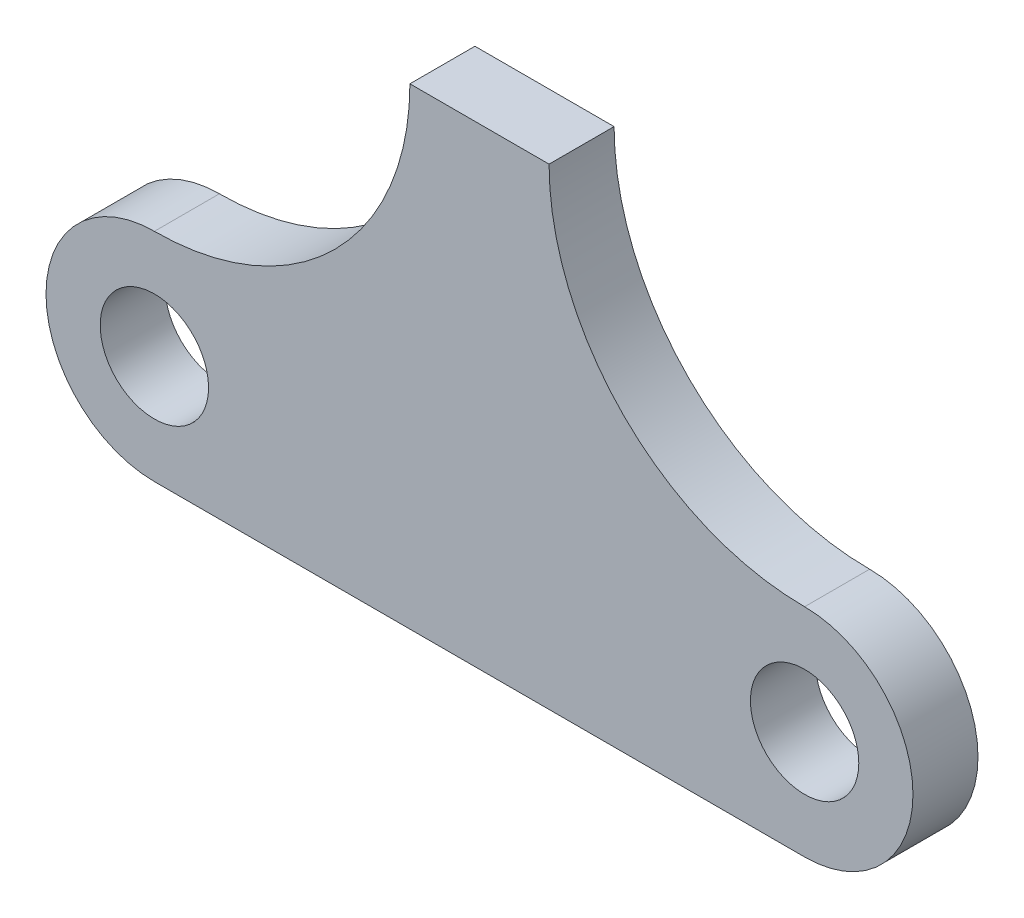
SolidWorks part; units mm, degrees
ref_plane "Front Plane" through (0, 0, 0) normal (0, 0, 1) x (1, 0, 0)
ref_plane "Top Plane" through (0, 0, 0) normal (0, 1, 0) x (1, 0, 0)
ref_plane "Right Plane" through (0, 0, 0) normal (1, 0, 0) x (0, 0, -1)
sketch "Sketch1" plane through (0, 0, 0) normal (0, 0, 1) x (1, 0, 0)
  line L0 (15, 0) -> (-15, 0) construction
  line L1 (15, -5) -> (-15, -5)
  line L2 (15, 5) -> (-15, 5)
  line L3 (-3.2101, 16.7899) -> (3.2101, 16.7899)
  arc A0 (15, -5) -> (15, 5) centre (15, 0) ccw
  arc A1 (-15, 5) -> (-15, -5) centre (-15, 0) ccw
  circle A2 centre (-15, 0) radius 2.5
  circle A3 centre (15, 0) radius 2.5
  arc A4 (-15, 5) -> (-3.2101, 16.7899) centre (-15, 16.7899) ccw
  arc A5 (15, 5) -> (3.2101, 16.7899) centre (15, 16.7899) cw
  point P2 (0, 0)
  point P16 (0, 0)
  dimension "D2" = 5
  dimension "D3" = 5
  dimension "D4" = 5
  dimension "D1" = 30
extrude "Boss-Extrude1" add sketch "Sketch1" along normal blind 3
